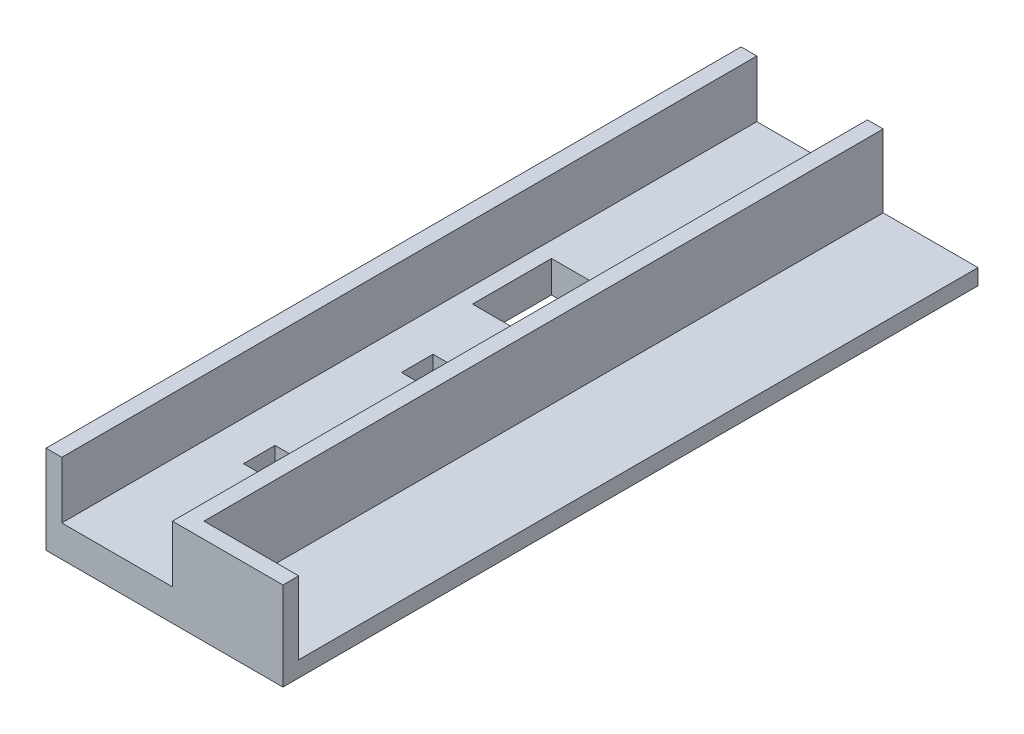
SolidWorks part; units mm, degrees
ref_plane "Płaszczyzna przednia" through (0, 0, 0) normal (0, 0, 1) x (1, 0, 0)
ref_plane "Płaszczyzna górna" through (0, 0, 0) normal (0, 1, 0) x (1, 0, 0)
ref_plane "Płaszczyzna prawa" through (0, 0, 0) normal (1, 0, 0) x (0, 0, -1)
sketch "Szkic1" plane through (0, 0, 0) normal (0, 0, 1) x (1, 0, 0)
  line L0 (0, 0) -> (0, 40.355) construction
  line L2 (17.5, 18) -> (-17.5, 18)
  line L3 (17.5, 18) -> (17.5, 0)
  line L4 (17.5, 0) -> (-17.5, 0)
  line L5 (-17.5, 18) -> (-17.5, 0)
  line L6 (17.5, 18) -> (-17.5, 0) construction
  line L7 (17.5, 0) -> (-17.5, 18) construction
  line L8 (17.5, 18) -> (22.5, 18)
  line L9 (52.5, -5) -> (22.5, -5)
  line L10 (52.5, -5) -> (52.5, 18)
  line L11 (52.5, 18) -> (22.5, 18)
  line L12 (22.5, -5) -> (22.5, 18)
  line L13 (52.5, -5) -> (22.5, 18) construction
  line L14 (52.5, 18) -> (22.5, -5) construction
  line L15 (-17.5, 18) -> (-22.5, 18)
  line L16 (-22.5, 18) -> (-22.5, -10)
  line L17 (-22.5, -10) -> (52.5, -10)
  line L18 (52.5, -10) -> (52.5, -5)
  point P3 (0, 9)
  point P17 (0, 0)
  dimension "D1" = 35
  dimension "D2" = 18
  dimension "D3" = 5
  dimension "D4" = 30
  dimension "D5" = 5
  dimension "D6" = 5
  dimension "D7" = 10
extrude "Dodanie-wyciągnięcie1" add sketch "Szkic1" against normal blind 220 contours L17 L18 L9 L12 L8 L3 L4 L5 L15 L16
sketch "Szkic4" plane through (0, 0, 0) normal (0, 0, 1) x (1, 0, 0)
  line L0 (52.5, -10) -> (52.5, -5) construction
  line L1 (22.5, -5) -> (52.5, -5)
  line L2 (22.5, -5) -> (22.5, 18)
  line L3 (22.5, 18) -> (52.5, 18)
  line L4 (52.5, -5) -> (52.5, 18)
  line L5 (17.5, 18) -> (22.5, 18) construction
extrude "Dodanie-wyciągnięcie3" add sketch "Szkic4" against normal blind 5
sketch "Szkic5" plane through (0, 0, 0) normal (0, 1, 0) x (1, 0, 0)
  line L0 (0, 0) -> (0, 220) construction
  line L1 (17.5, 220) -> (-17.5, 220) construction
  line L2 (17.5, 0) -> (-17.5, 0) construction
  line L3 (5, 45) -> (-5, 45)
  line L4 (5, 45) -> (5, 55)
  line L5 (5, 55) -> (-5, 55)
  line L6 (-5, 45) -> (-5, 55)
  line L7 (5, 45) -> (-5, 55) construction
  line L8 (5, 55) -> (-5, 45) construction
  line L10 (5, 105) -> (-5, 105)
  line L11 (5, 105) -> (5, 95)
  line L12 (5, 95) -> (-5, 95)
  line L13 (-5, 105) -> (-5, 95)
  line L14 (5, 105) -> (-5, 95) construction
  line L15 (5, 95) -> (-5, 105) construction
  line L16 (12.5, 150) -> (-12.5, 150)
  line L17 (12.5, 150) -> (12.5, 125)
  line L18 (12.5, 125) -> (-12.5, 125)
  line L19 (-12.5, 150) -> (-12.5, 125)
  line L20 (12.5, 150) -> (-12.5, 125) construction
  line L21 (12.5, 125) -> (-12.5, 150) construction
  point P5 (0, 50)
  point P10 (0, 137.5)
  point P13 (0, 100)
  dimension "D1" = 10
  dimension "D2" = 45
  dimension "D3" = 50
  dimension "D4" = 20
  dimension "D5" = 25
extrude "Wytnij-wyciągnięcie1" cut sketch "Szkic5" against normal blind 25
